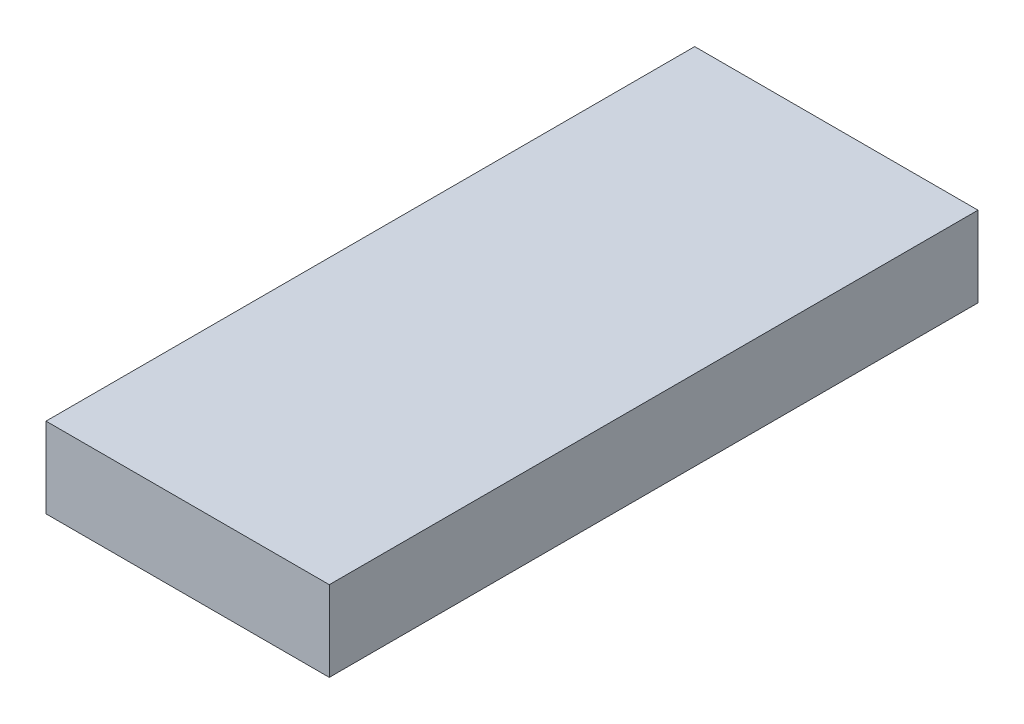
SolidWorks part; units mm, degrees
ref_plane "Front Plane" through (0, 0, 0) normal (0, 0, 1) x (1, 0, 0)
ref_plane "Top Plane" through (0, 0, 0) normal (0, 1, 0) x (1, 0, 0)
ref_plane "Right Plane" through (0, 0, 0) normal (1, 0, 0) x (0, 0, -1)
sketch "Sketch1" plane through (0, 0, 0) normal (0, 1, 0) x (1, 0, 0)
  line L1 (-31.75, 72.7) -> (31.75, 72.7)
  line L2 (-31.75, 72.7) -> (-31.75, -72.7)
  line L3 (-31.75, -72.7) -> (31.75, -72.7)
  line L4 (31.75, 72.7) -> (31.75, -72.7)
  line L5 (-31.75, 72.7) -> (31.75, -72.7) construction
  line L6 (-31.75, -72.7) -> (31.75, 72.7) construction
  point P0 (0, 0)
  dimension "D1" = 63.5
  dimension "D2" = 145.4
extrude "Boss-Extrude1" add sketch "Sketch1" along normal blind 18
sketch "Sketch3" plane through (0, 0, 0) normal (0, -1, 0) x (1, 0, 0)
  line L0 (-31.75, 72.7) -> (31.75, 72.7) construction
  line L1 (31.75, 72.7) -> (31.75, -72.7) construction
  circle A0 centre (10.75, -29.1) radius 0.75
  circle A1 centre (10.75, -31.64) radius 0.75
  circle A2 centre (10.75, -34.18) radius 0.75
  circle A3 centre (10.75, -36.72) radius 0.75
  dimension "D1" = 1.5
  dimension "D2" = 101.8
  dimension "D3" = 21
  dimension "D4" = 4
extrude "Cut-Extrude2" cut sketch "Sketch3" against normal blind 8 and the other way through all
sketch "Sketch4" plane through (0, 0, 0) normal (0, -1, 0) x (1, 0, 0)
  line L0 (-31.75, -72.7) -> (-31.75, 72.7) construction
  line L1 (-14.35, -57.4) -> (0.65, -57.4)
  line L2 (-14.35, -57.4) -> (-14.35, -63.1)
  line L3 (-14.35, -63.1) -> (0.65, -63.1)
  line L4 (0.65, -57.4) -> (0.65, -63.1)
  line L5 (-14.35, -57.4) -> (0.65, -63.1) construction
  line L6 (-14.35, -63.1) -> (0.65, -57.4) construction
  line L7 (31.75, -72.7) -> (-31.75, -72.7) construction
  point P0 (-6.85, -60.25)
  dimension "D1" = 15
  dimension "D2" = 32.4
  dimension "D3" = 5.7
  dimension "D4" = 15.3
extrude "Boss-Extrude2" add sketch "Sketch4" along normal blind 1
